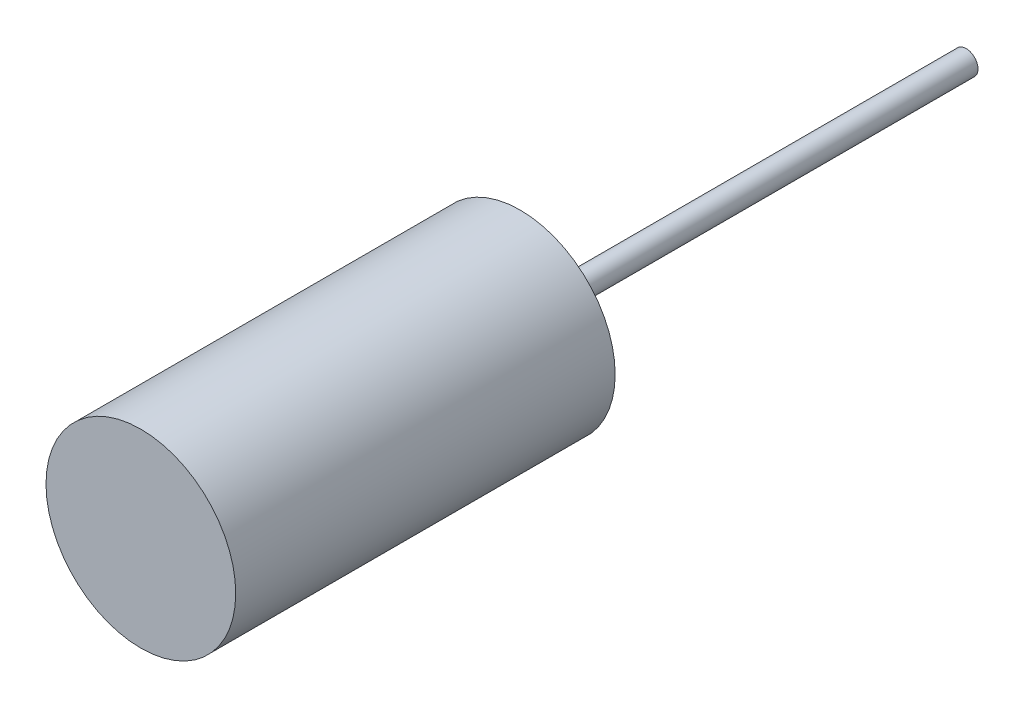
SolidWorks part; units mm, degrees
ref_plane "Front Plane" through (0, 0, 0) normal (0, 0, 1) x (1, 0, 0)
ref_plane "Top Plane" through (0, 0, 0) normal (0, 1, 0) x (1, 0, 0)
ref_plane "Right Plane" through (0, 0, 0) normal (1, 0, 0) x (0, 0, -1)
sketch "Sketch1" plane through (0, 0, 0) normal (0, 0, 1) x (1, 0, 0)
  circle A0 centre (0, 0) radius 12.7
  dimension "D1" = 25.4
extrude "Boss-Extrude1" add sketch "Sketch1" along normal blind 50.8
sketch "Sketch2" plane through (0, 0, 0) normal (0, 0, -1) x (-1, 0, 0)
  circle A0 centre (0, 0) radius 1.5875
  dimension "D1" = 3.175
extrude "Boss-Extrude2" add sketch "Sketch2" along normal blind 59.69
sketch "Sketch3" plane through (0, 0, 0) normal (0, 0, -1) x (-1, 0, 0)
  line L1 (-10.16, 7.62) -> (10.16, 7.62) construction
  line L2 (-10.16, 7.62) -> (-10.16, -7.62) construction
  line L3 (-10.16, -7.62) -> (10.16, -7.62) construction
  line L4 (10.16, 7.62) -> (10.16, -7.62) construction
  line L5 (-10.16, 7.62) -> (10.16, -7.62) construction
  line L6 (-10.16, -7.62) -> (10.16, 7.62) construction
  circle A0 centre (0, 0) radius 12.7 construction
  point P0 (0, 0)
  dimension "D1" = 15.24
hole_wizard "#2-64 Tapped Hole1" positions "Sketch7" profile "Sketch6" tap size "#2-64" standard "ANSI Inch"
sketch "Sketch7" plane through (0, 0, 0) normal (0, 0, -1) x (-1, 0, 0)
  line L0 (-10.16, 7.62) -> (10.16, 7.62) construction
  line L1 (-10.16, -7.62) -> (10.16, -7.62) construction
  point P0 (-7.62, 7.62)
  point P4 (7.62, 7.62)
  point P6 (7.62, -7.62)
  point P10 (-7.62, -7.62)
  dimension "D1" = 7.62
  dimension "D2" = 7.62
  dimension "D3" = 7.62
  dimension "D4" = 7.62
sketch "Sketch6" plane through (7.62, 7.62, 0) normal (1, 0, 0) x (0, 1, 0)
  line L0 (0, 0) -> (0, 13.2342)
  line L1 (0, 13.2342) -> (0.889, 12.7)
  line L2 (0.889, 12.7) -> (0.889, 0)
  line L5 (0.889, 0) -> (0, 0)
  line L10 (0, 13.2342) -> (-0.889, 12.7) construction
  line L11 (0, -6.35) -> (0, 107.95) construction
  dimension "Tap Drill Dia." = 1.778
  dimension "Tap Drill Depth" = 12.7
  dimension "Drill Angle" = 118
